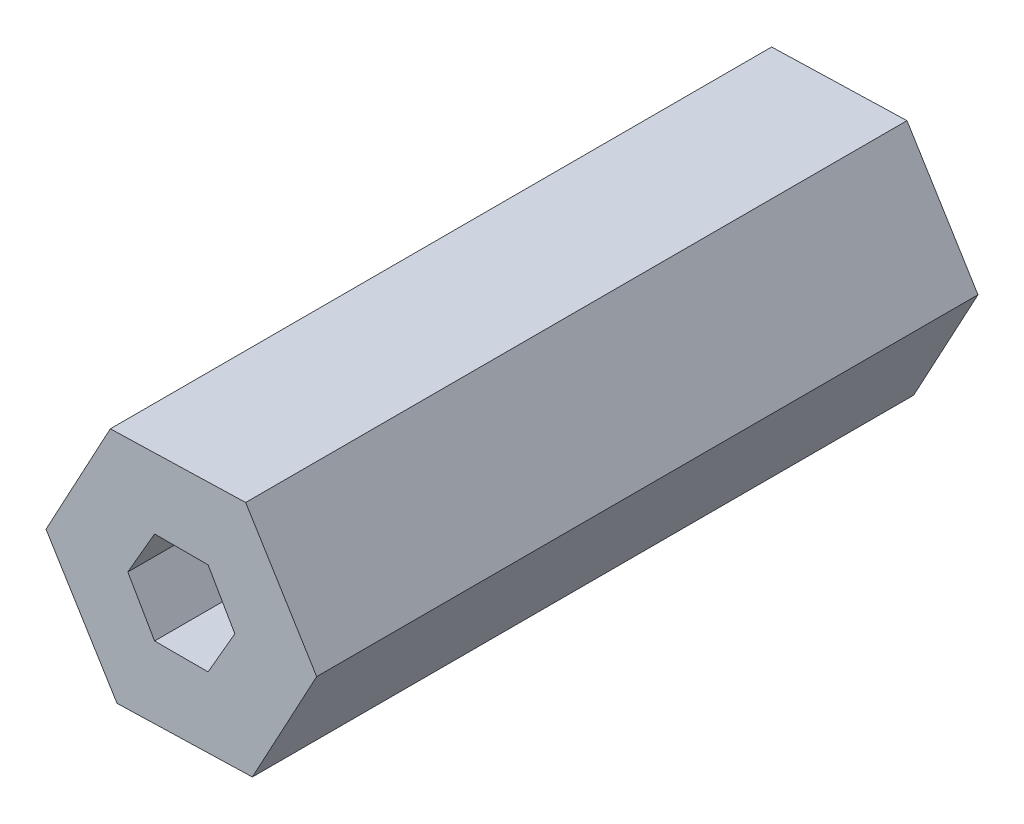
SolidWorks part; units mm, degrees
ref_plane "Front Plane" through (0, 0, 0) normal (0, 0, 1) x (1, 0, 0)
ref_plane "Top Plane" through (0, 0, 0) normal (0, 1, 0) x (1, 0, 0)
ref_plane "Right Plane" through (0, 0, 0) normal (1, 0, 0) x (0, 0, -1)
sketch "Sketch3" plane through (0, 0, 0) normal (0, 0, 1) x (1, 0, 0)
  line L1 (2.8983, 0) -> (1.4491, 2.51)
  line L2 (1.4491, 2.51) -> (-1.4491, 2.51)
  line L3 (-1.4491, 2.51) -> (-2.8983, 0)
  line L4 (-2.8983, 0) -> (-1.4491, -2.51)
  line L5 (-1.4491, -2.51) -> (1.4491, -2.51)
  line L6 (1.4491, -2.51) -> (2.8983, 0)
  line L7 (4.613, 0) -> (2.3065, 3.995)
  line L8 (2.3065, 3.995) -> (-2.3065, 3.995)
  line L9 (-2.3065, 3.995) -> (-4.613, 0)
  line L10 (-4.613, 0) -> (-2.3065, -3.995)
  line L11 (-2.3065, -3.995) -> (2.3065, -3.995)
  line L12 (2.3065, -3.995) -> (4.613, 0)
  line L13 (7.3294, 0.2091) -> (3.4836, 6.452)
  line L14 (3.4836, 6.452) -> (-3.8458, 6.2428)
  line L15 (-3.8458, 6.2428) -> (-7.3294, -0.2091)
  line L16 (-7.3294, -0.2091) -> (-3.4836, -6.452)
  line L17 (-3.4836, -6.452) -> (3.8458, -6.2428)
  line L18 (3.8458, -6.2428) -> (7.3294, 0.2091)
  circle A0 centre (0, 0) radius 2.51 construction
  circle A1 centre (0, 0) radius 3.995 construction
  circle A2 centre (0, 0) radius 6.35 construction
sketch "Sketch4" plane through (0, 0, 0) normal (0, 0, 1) x (1, 0, 0)
  line L1 (2.8983, 0) -> (1.4491, 2.51)
  line L2 (1.4491, 2.51) -> (-1.4491, 2.51)
  line L3 (-1.4491, 2.51) -> (-2.8983, 0)
  line L4 (-2.8983, 0) -> (-1.4491, -2.51)
  line L5 (-1.4491, -2.51) -> (1.4491, -2.51)
  line L6 (1.4491, -2.51) -> (2.8983, 0)
  line L7 (4.613, 0) -> (2.3065, 3.995)
  line L8 (2.3065, 3.995) -> (-2.3065, 3.995)
  line L9 (-2.3065, 3.995) -> (-4.613, 0)
  line L10 (-4.613, 0) -> (-2.3065, -3.995)
  line L11 (-2.3065, -3.995) -> (2.3065, -3.995)
  line L12 (2.3065, -3.995) -> (4.613, 0)
  line L13 (7.3294, 0.2091) -> (3.4836, 6.452)
  line L14 (3.4836, 6.452) -> (-3.8458, 6.2428)
  line L15 (-3.8458, 6.2428) -> (-7.3294, -0.2091)
  line L16 (-7.3294, -0.2091) -> (-3.4836, -6.452)
  line L17 (-3.4836, -6.452) -> (3.8458, -6.2428)
  line L18 (3.8458, -6.2428) -> (7.3294, 0.2091)
  circle A0 centre (0, 0) radius 2.51 construction
  circle A1 centre (0, 0) radius 3.995 construction
  circle A2 centre (0, 0) radius 6.35 construction
extrude "Boss-Extrude2" add sketch "Sketch4" along normal blind 35.814 contours L17 L18 L13 L14 L15 L16 L12 L11 L10 L9 L8 L7 | L11 L12 L7 L8 L9 L10 L6 L5 L4 L3 L2 L1
